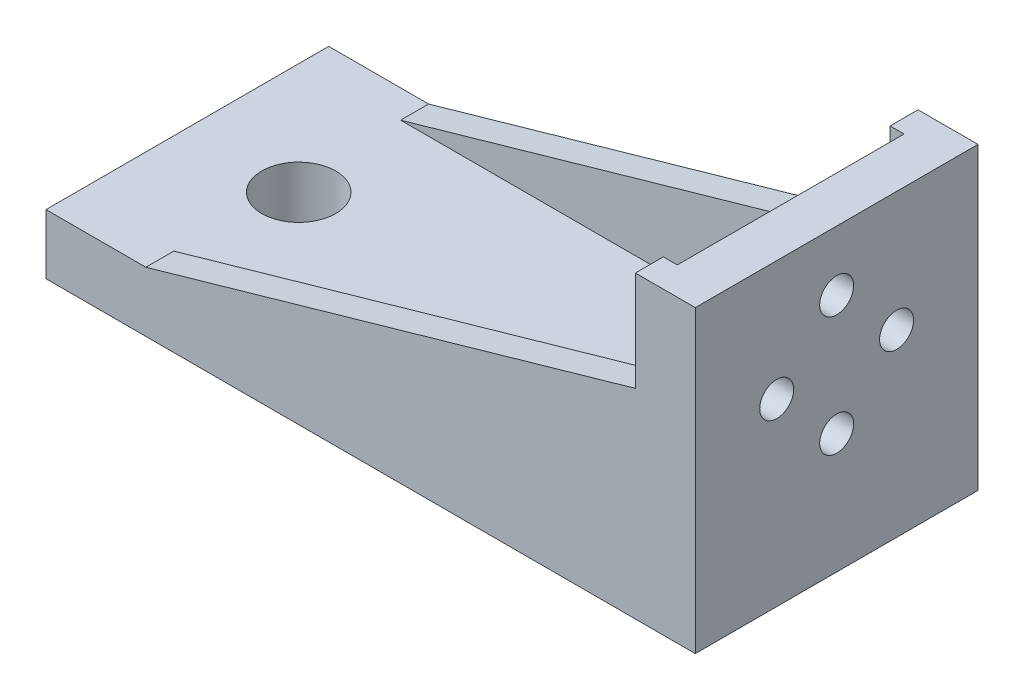
SolidWorks part; units mm, degrees
material "聚脂树脂"
ref_plane "前视基准面" through (0, 0, 0) normal (0, 0, 1) x (1, 0, 0)
ref_plane "上视基准面" through (0, 0, 0) normal (0, 1, 0) x (1, 0, 0)
ref_plane "右视基准面" through (0, 0, 0) normal (1, 0, 0) x (0, 0, -1)
other "Configuration Table"
sketch "草图1" plane through (0, 0, 0) normal (0, 0, 1) x (1, 0, 0)
  line L0 (0, 0) -> (65, 0)
  line L1 (65, 0) -> (65, 30)
  line L2 (65, 30) -> (59, 30)
  line L3 (59, 30) -> (59, 20)
  line L4 (59, 20) -> (10, 6)
  line L5 (10, 6) -> (0, 6)
  line L6 (0, 6) -> (0, 0)
  dimension "D1" = 30
  dimension "D2" = 6
  dimension "D3" = 10
  dimension "D4" = 65
extrude "凸台-拉伸1" add sketch "草图1" along normal mid plane 28.3
sketch "草图2" plane through (0, 0, 0) normal (0, 0, 1) x (1, 0, 0)
  line L0 (0, 6) -> (60.4, 6)
  line L1 (0, 6) -> (0, 0) construction
  line L2 (60.4, 6) -> (60.4, 30)
  line L3 (65, 30) -> (59, 30) construction
  line L4 (60.4, 30) -> (0, 30)
  line L5 (0, 30) -> (0, 6)
  line L6 (65, 0) -> (65, 30) construction
  line L7 (10, 6) -> (0, 6) construction
  dimension "D1" = 4.6
extrude "切除-拉伸1" cut sketch "草图2" along normal mid plane 22.7
sketch "草图4" plane through (0, 0, 0) normal (0, 1, 0) x (1, 0, 0)
  line L0 (-5.3812, 0) -> (45.3159, 0) construction
  line L4 (65, -14.15) -> (65, 14.15) construction
  circle A2 centre (50.85, 0) radius 2.55
  circle A3 centre (11.15, 0) radius 3.7
  dimension "D1" = 5.1
  dimension "D2" = 7.4
  dimension "D3" = 14.15
  dimension "D4" = 39.7
extrude "切除-拉伸2" cut sketch "草图4" along normal up to next
sketch "草图5" plane through (0, 0, 0) normal (1, 0, 0) x (0, 0, -1)
  line L0 (0, 44.9599) -> (0, -4.5954) construction
  line L3 (-27.1727, 18) -> (23.77, 18) construction
  line L4 (-14.15, 30) -> (14.15, 30) construction
  circle A2 centre (0, 24) radius 1.7
  circle A3 centre (0, 12) radius 1.7
  circle A4 centre (-6, 18) radius 1.7
  circle A5 centre (6, 18) radius 1.7
  dimension "D1" = 3.4
  dimension "D2" = 3.4
  dimension "D3" = 6
  dimension "D4" = 12
  dimension "D5" = 12
  dimension "D6" = 6
extrude "切除-拉伸3" cut sketch "草图5" along normal up to next
